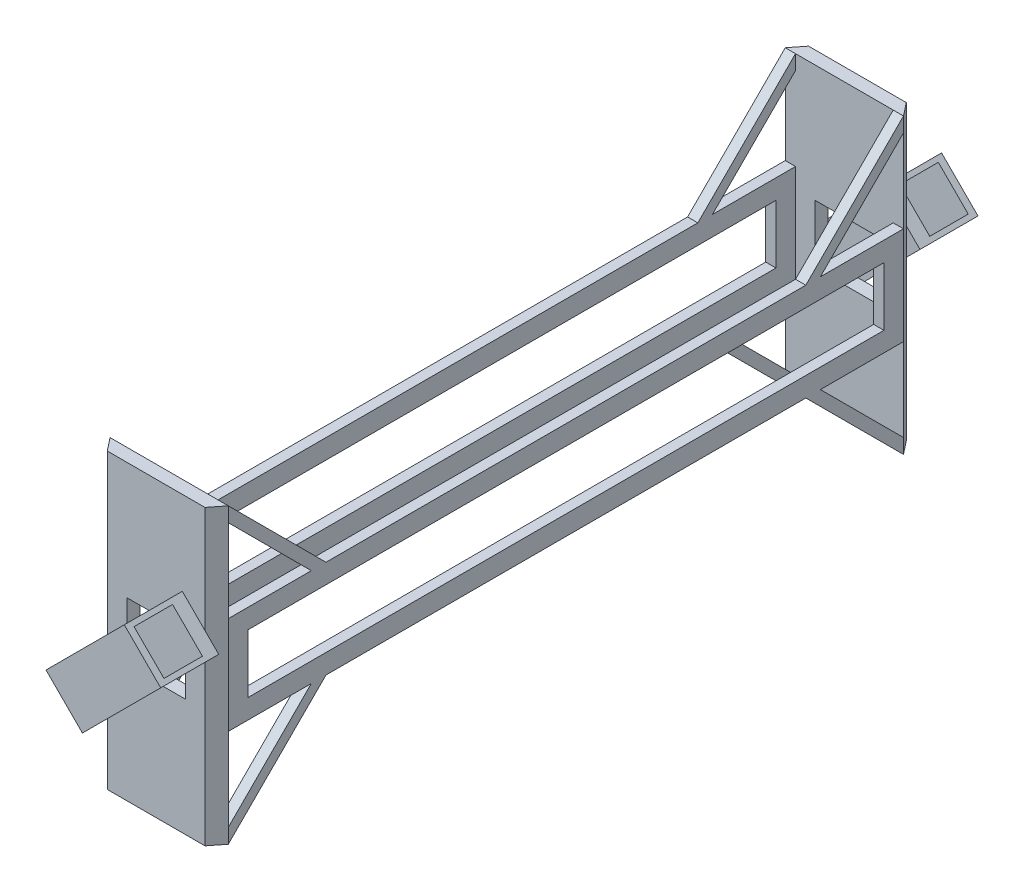
SolidWorks part; units mm, degrees
material "AISI 4130 Steel, normalized at 870C"
ref_plane "Front Plane" through (0, 0, 0) normal (0, 0, 1) x (1, 0, 0)
ref_plane "Top Plane" through (0, 0, 0) normal (0, 1, 0) x (1, 0, 0)
ref_plane "Right Plane" through (0, 0, 0) normal (1, 0, 0) x (0, 0, -1)
sketch "Sketch1" plane through (0, 0, 0) normal (0, 0, 1) x (1, 0, 0)
  line L1 (-19.05, -19.05) -> (19.05, -19.05)
  line L2 (-19.05, -19.05) -> (-19.05, 19.05)
  line L3 (-19.05, 19.05) -> (19.05, 19.05)
  line L4 (19.05, -19.05) -> (19.05, 19.05)
  dimension "D1" = 19.05
  dimension "D2" = 19.05
  dimension "D3" = 19.05
  dimension "D4" = 19.05
extrude "Boss-Extrude1" add sketch "Sketch1" along normal blind 5.08
sketch "Sketch2" plane through (0, 0, 0) normal (0, 0, -1) x (-1, 0, 0)
  line L8 (-19.05, -19.05) -> (-16.9, -19.05)
  line L9 (-16.9, -19.05) -> (-19.05, -19.05)
  line L10 (0, 55) -> (0, -55) construction
  line L11 (-19.05, 19.05) -> (-16.9, 19.05)
  line L12 (-16.9, 19.05) -> (-19.05, 19.05)
  line L15 (19.05, 19.05) -> (23.05, 19.05)
  line L16 (-19.05, -19.05) -> (-23.05, -19.05)
  line L17 (-19.05, -19.05) -> (-19.05, 19.05)
  line L18 (-19.05, 19.05) -> (-23.05, 19.05)
  line L19 (-23.05, -19.05) -> (-23.05, 19.05)
  line L20 (23.05, -19.05) -> (23.05, 19.05)
  line L21 (19.05, -19.05) -> (23.05, -19.05)
  line L22 (19.05, -19.05) -> (19.05, 19.05)
  line M10 (19.05, -19.05) -> (19.05, 19.05)
  line M12 (-19.05, 19.05) -> (-19.05, -19.05)
  dimension "D2" = 4
extrude "Boss-Extrude2" add sketch "Sketch2" along normal blind 263.3104 separate body contours L19 L16 L8 L11 L18 M12 | L21 L20 L15 M10
sketch "Sketch4" plane through (0, 19.05, 0) normal (0, 1, 0) x (1, 0, 0)
  line L0 (23.05, 0) -> (19.05, -5.08)
  line L1 (19.05, -5.08) -> (19.05, 0)
  line L2 (19.05, 0) -> (23.05, 0)
  line L3 (-19.05, 0) -> (-19.05, -5.08)
  line L4 (-19.05, -5.08) -> (-23.05, 0)
  line L5 (-23.05, 0) -> (-19.05, 0)
extrude "Boss-Extrude4" add sketch "Sketch4" against normal up to vertex (38.1 mm away) up to point (23.05, -19.05, 0)
ref_plane "Plane4" through (0, 0, -131.6552) normal (0, 0, -1) x (-1, 0, 0)
mirror "Mirror2" about plane through (0, 0, -131.6552) normal (0, 0, -1) of bodies 106
sketch "Sketch5" plane through (0, 0, 5.08) normal (0, 0, 1) x (1, 0, 0)
  line L0 (19.05, 19.05) -> (-19.05, 19.05) construction
  line L1 (-11.43, 11.43) -> (11.43, 11.43)
  line L2 (-11.43, 11.43) -> (-11.43, -11.43)
  line L3 (-11.43, -11.43) -> (11.43, -11.43)
  line L4 (11.43, 11.43) -> (11.43, -11.43)
  line L5 (-19.05, -19.05) -> (19.05, -19.05) construction
  line L6 (19.05, -19.05) -> (19.05, 19.05) construction
  line L7 (-19.05, 19.05) -> (-19.05, -19.05) construction
  dimension "D1" = 7.62
  dimension "D2" = 7.62
  dimension "D3" = 7.62
  dimension "D4" = 7.62
extrude "Cut-Extrude1" cut sketch "Sketch5" against normal blind 354.2424
sketch "Sketch6" plane through (-23.05, 0, 0) normal (-1, 0, 0) x (0, 0, 1)
  line L0 (-263.3104, -19.05) -> (-263.3104, 19.05) construction
  line L1 (-255.6904, -11.43) -> (-7.62, -11.43)
  line L2 (-255.6904, -11.43) -> (-255.6904, 11.43)
  line L3 (-255.6904, 11.43) -> (-7.62, 11.43)
  line L4 (-7.62, -11.43) -> (-7.62, 11.43)
  line L5 (-263.3104, 19.05) -> (0, 19.05) construction
  line L6 (-263.3104, -19.05) -> (0, -19.05) construction
  dimension "D1" = 7.62
  dimension "D2" = 7.62
  dimension "D3" = 7.62
  dimension "D4" = 7.62
extrude "Cut-Extrude2" cut sketch "Sketch6" against normal blind 354.2424
sketch "Sketch7" plane through (0, 19.05, 0) normal (0, 1, 0) x (1, 0, 0)
  line L0 (-19.05, 0) -> (-23.05, 0)
  line L1 (19.05, -5.08) -> (-19.05, -5.08)
  line L3 (19.05, 0) -> (-19.05, 0)
  line L5 (-23.05, 0) -> (-19.05, -5.08)
  line L6 (19.05, -5.08) -> (23.05, 0)
  line L7 (23.05, 0) -> (19.05, 0)
  line L8 (20.955, 131.6552) -> (-20.955, 131.6552) construction
  line L9 (19.05, 268.3904) -> (23.05, 263.3104)
  line L10 (23.05, 263.3104) -> (19.05, 263.3104)
  line L11 (19.05, 263.3104) -> (-19.05, 263.3104)
  line L12 (-19.05, 263.3104) -> (-23.05, 263.3104)
  line L13 (-23.05, 263.3104) -> (-19.05, 268.3904)
  line L14 (19.05, 268.3904) -> (-19.05, 268.3904)
extrude "Boss-Extrude5" add sketch "Sketch7" along normal blind 38.1
sketch "Sketch8" plane through (-23.05, 0, 0) normal (-1, 0, 0) x (0, 0, 1)
  line L0 (0, 57.15) -> (-38.1, 19.05)
  line L1 (-263.3104, 19.05) -> (0, 19.05) construction
  line L2 (-38.1, 19.05) -> (-32.3956, 19.05)
  line L3 (-32.3956, 19.05) -> (0, 51.4456)
  line L4 (0, 57.15) -> (0, 19.05) construction
  line L5 (0, 51.4456) -> (0, 57.15)
  line L6 (-131.6552, 20.955) -> (-131.6552, -20.955) construction
  line L7 (-230.9148, 19.05) -> (-263.3104, 51.4456)
  line L8 (-225.2104, 19.05) -> (-230.9148, 19.05)
  line L9 (-263.3104, 57.15) -> (-225.2104, 19.05)
  line L10 (-263.3104, 51.4456) -> (-263.3104, 57.15)
extrude "Boss-Extrude6" add sketch "Sketch8" against normal blind 4
mirror "Mirror8" about plane through (0, 0, 0) normal (1, 0, 0) of "Boss-Extrude6"
mirror "Mirror9" about plane through (0, 0, 0) normal (0, 1, 0) of "Boss-Extrude5", "Boss-Extrude6", "Mirror8"
sketch "Sketch11" plane through (0, 0, 5.08) normal (0, 0, 1) x (1, 0, 0)
  line L8 (-18.5294, -7.9228) -> (-7.9228, -18.5294)
  line L9 (-18.5294, -7.9228) -> (-20.3254, -6.1267)
  line L10 (-20.3254, -6.1267) -> (8.4114, 22.6101)
  line L11 (8.4114, 22.6101) -> (10.2075, 24.4062)
  line L12 (10.2075, 24.4062) -> (24.4062, 10.2075)
  line L13 (24.4062, 10.2075) -> (-6.1267, -20.3254)
  line L14 (-6.1267, -20.3254) -> (-7.9228, -18.5294)
extrude "Boss-Extrude8" add sketch "Sketch11" along normal blind 5.08
sketch "Sketch12" plane through (0, 0, 10.16) normal (0, 0, 1) x (1, 0, 0)
  line L0 (24.4062, 10.2075) -> (-6.1267, -20.3254)
  line L1 (-6.1267, -20.3254) -> (24.4062, 10.2075) construction
  line L2 (-20.3254, -6.1267) -> (-6.1267, -20.3254) construction
  line L3 (-6.1267, -20.3254) -> (-20.3254, -6.1267)
  line L4 (-20.3254, -6.1267) -> (10.2075, 24.4062)
  line L5 (10.2075, 24.4062) -> (11.4775, 23.1362)
  line L6 (21.8662, 10.2075) -> (23.1362, 11.4775)
  line L7 (-6.1267, -17.7854) -> (-17.7854, -6.1267)
  line L8 (-17.7854, -6.1267) -> (10.2075, 21.8662)
  line L10 (21.8662, 10.2075) -> (-6.1267, -17.7854)
  line L11 (10.2075, 21.8662) -> (11.4775, 23.1362)
  line L12 (23.1362, 11.4775) -> (24.4062, 10.2075)
extrude "Boss-Extrude9" add sketch "Sketch12" along normal blind 15
sketch "Sketch13" plane through (0, 0, 25.16) normal (0, 0, 1) x (1, 0, 0)
  line L0 (-20.3254, -6.1267) -> (10.2075, 24.4062)
  line L1 (10.2075, 24.4062) -> (24.4062, 10.2075)
  line L2 (24.4062, 10.2075) -> (-6.1267, -20.3254)
  line L3 (-6.1267, -20.3254) -> (-20.3254, -6.1267)
extrude "Boss-Extrude10" add sketch "Sketch13" along normal blind 2.54
mirror "Mirror12" about plane through (0, 0, -131.6552) normal (0, 0, -1) of "Boss-Extrude8", "Boss-Extrude9", "Boss-Extrude10"
